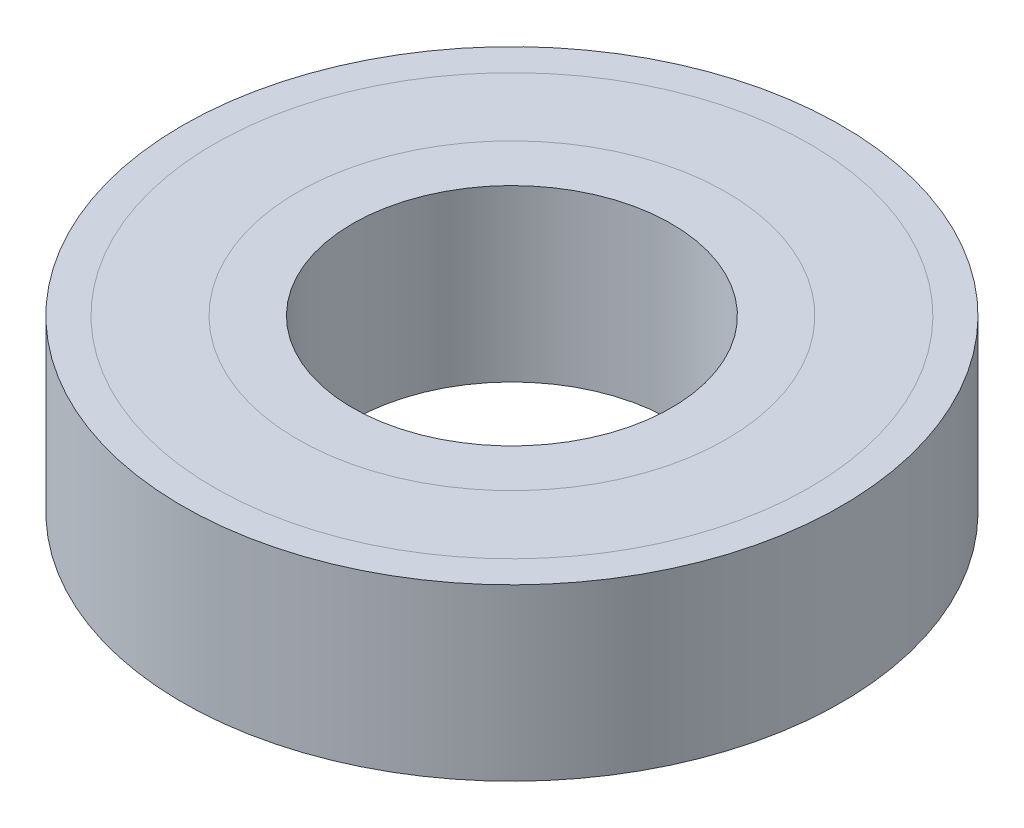
SolidWorks part; units mm, degrees
other "Markup1"
sketch "Sketch2" plane through (-62, 8, 62) normal (-0.7232, 0.6558, 0.2165) x (0.3413, 0.6119, -0.7135)
sketch "Sketch3" plane through (-31, 8, 31) normal (-0.7232, 0.6558, 0.2165) x (0.3413, 0.6119, -0.7135)
sketch "Sketch5" plane through (-31, 8, 31) normal (-0.7232, 0.6558, 0.2165) x (0.3413, 0.6119, -0.7135)
sketch "Sketch6" plane through (-31, 8, 31) normal (-0.7232, 0.6558, 0.2165) x (0.3413, 0.6119, -0.7135)
ref_plane "Front Plane" through (0, 0, 0) normal (0, 0, 1) x (1, 0, 0)
ref_plane "Top Plane" through (0, 0, 0) normal (0, 1, 0) x (1, 0, 0)
ref_plane "Right Plane" through (0, 0, 0) normal (1, 0, 0) x (0, 0, -1)
sketch "Sketch1" plane through (0, 0, 0) normal (0, 0, 1) x (1, 0, 0)
  line L0 (0, 0) -> (15, 0) construction
  line L1 (0, 8) -> (0, -8) construction
  line L2 (15, -8) -> (31, -8)
  line L3 (15, -8) -> (15, 8)
  line L4 (15, 8) -> (31, 8)
  line L5 (31, -8) -> (31, 8)
  line L6 (15, -8) -> (31, 8) construction
  line L7 (15, 8) -> (31, -8) construction
  point P2 (23, 0)
  point P4 (0, 0)
  point P10 (0, 0)
  point P11 (15, 0)
  point P15 (31, 0)
  dimension "D3" = 16
  dimension "D1" = 15
  dimension "D2" = 31
revolve "Revolve1" add sketch "Sketch1" angle 360 about L1
sketch "Sketch4" plane through (0, 0, 0) normal (0, 1, 0) x (1, 0, 0)
  circle A0 centre (0, 0) radius 28
  circle A1 centre (0, 0) radius 20.15
  dimension "D1" = 56
  dimension "D2" = 40.3
split line "Split Line1"
equation "\"OD\"= 62mm"
equation "\"ID\"= 30mm"
equation "\"Depth\"= 16mm"
equation "\"D3@Sketch1\"=\"Depth\""
equation "\"D1@Sketch1\"=\"ID\"/2"
equation "\"D2@Sketch1\"=\"OD\"/2"
equation "\"OD Abutment\"= 56mm"
equation "\"ID Abutment\"= 40.3mm"
equation "\"D1@Sketch4\"=\"OD Abutment\""
equation "\"D2@Sketch4\"=\"ID Abutment\""
